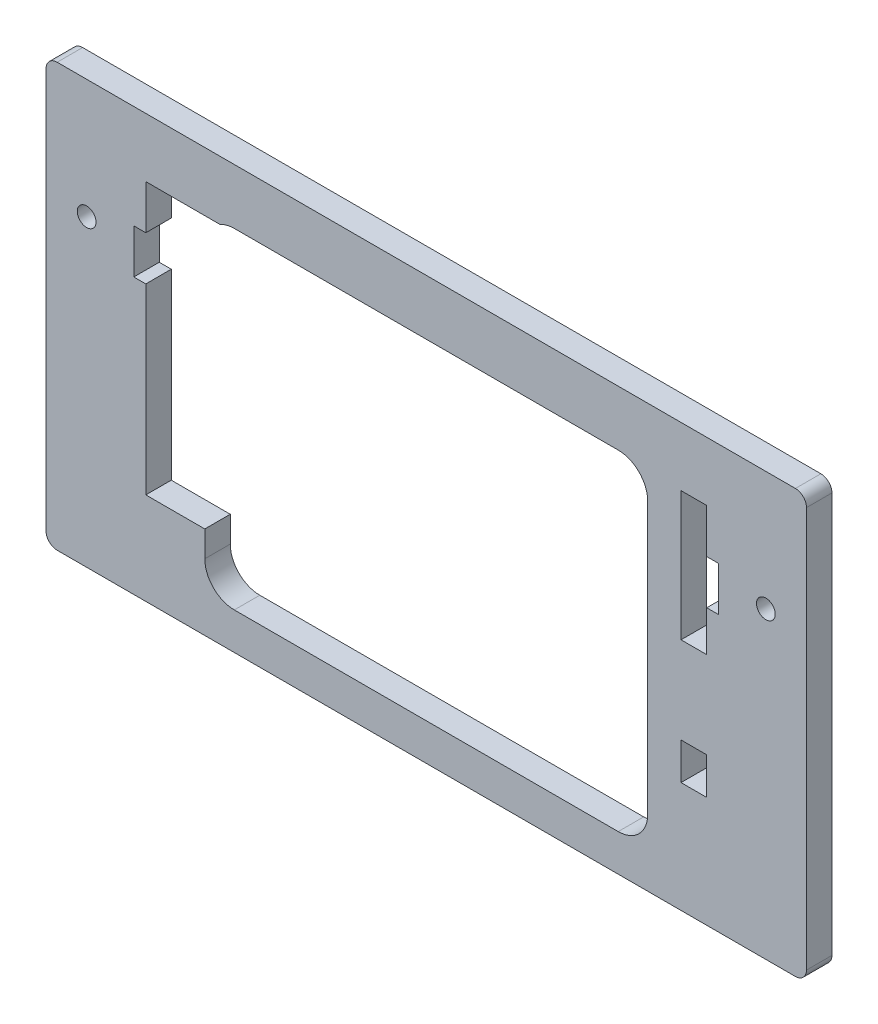
SolidWorks part; units mm, degrees
ref_plane "Front Plane" through (0, 0, 0) normal (0, 0, 1) x (1, 0, 0)
ref_plane "Top Plane" through (0, 0, 0) normal (0, 1, 0) x (1, 0, 0)
ref_plane "Right Plane" through (0, 0, 0) normal (1, 0, 0) x (0, 0, -1)
sketch "Sketch1" plane through (0, 0, 0) normal (0, 0, 1) x (1, 0, 0)
  line L1 (103, 57.25) -> (-103, 57.25)
  line L2 (103, 57.25) -> (103, -57.25)
  line L3 (103, -57.25) -> (-103, -57.25)
  line L4 (-103, 57.25) -> (-103, -57.25)
  line L5 (103, 57.25) -> (-103, -57.25) construction
  line L6 (103, -57.25) -> (-103, 57.25) construction
  point P0 (0, 0)
  dimension "D1" = 114.5
  dimension "D2" = 206
extrude "Boss-Extrude1" add sketch "Sketch1" against normal blind 6.9
sketch "Sketch2" plane through (0, 0, 0) normal (0, 0, 1) x (1, 0, 0)
  line L0 (103, 57.25) -> (-103, 57.25) construction
  line L1 (60, -45.75) -> (-60, -45.75)
  line L2 (60, -45.75) -> (60, 42.25)
  line L3 (60, 42.25) -> (-60, 42.25)
  line L4 (-60, -45.75) -> (-60, 42.25)
  line L5 (60, -45.75) -> (-60, 42.25) construction
  line L6 (60, 42.25) -> (-60, -45.75) construction
  point P0 (0, -1.75)
  dimension "D1" = 15
  dimension "D2" = 88
  dimension "D3" = 120
extrude "Cut-Extrude1" cut sketch "Sketch2" against normal through all
fillet "Fillet1" radius 8 4 edges at (60, 42.25, -3.45) (60, -45.75, -3.45) (-60, -45.75, -3.45) (-60, 42.25, -3.45)
sketch "Sketch3" plane through (0, 0, 0) normal (0, 0, 1) x (1, 0, 0)
  line L0 (103, 57.25) -> (-103, 57.25) construction
  line L1 (-91.775, 78.25) -> (-88.225, 78.25)
  line L2 (-91.775, 78.25) -> (-91.775, 36.25)
  line L3 (-91.775, 36.25) -> (-88.225, 36.25)
  line L4 (-88.225, 78.25) -> (-88.225, 36.25)
  line L5 (-91.775, 78.25) -> (-88.225, 36.25) construction
  line L6 (-91.775, 36.25) -> (-88.225, 78.25) construction
  point P0 (-90, 57.25)
  dimension "D1" = 3.55
  dimension "D2" = 21
  dimension "D3" = 90
extrude "Cut-Extrude2" [suppressed] cut sketch "Sketch3" against normal through all
sketch "Sketch4" plane through (0, 0, 0) normal (0, 0, 1) x (1, 0, 0)
  line L0 (103, 57.25) -> (-103, 57.25) construction
  line L1 (-93.81, 46.25) -> (-86.19, 46.25)
  line L2 (-93.81, 46.25) -> (-93.81, 41.25)
  line L3 (-93.81, 41.25) -> (-86.19, 41.25)
  line L4 (-86.19, 46.25) -> (-86.19, 41.25)
  line L5 (-93.81, 46.25) -> (-86.19, 41.25) construction
  line L6 (-93.81, 41.25) -> (-86.19, 46.25) construction
  point P0 (-90, 43.75)
  dimension "D1" = 7.62
  dimension "D2" = 5
  dimension "D3" = 11
extrude "Cut-Extrude3" [suppressed] cut sketch "Sketch4" against normal through all
sketch "Sketch5" plane through (0, 0, 0) normal (0, 0, 1) x (1, 0, 0)
  line L0 (103, 57.25) -> (-103, 57.25) construction
  line L1 (-65, 57.25) -> (-50, 57.25)
  line L2 (-65, 57.25) -> (-65, 63.75)
  line L3 (-65, 63.75) -> (-50, 63.75)
  line L4 (-50, 57.25) -> (-50, 63.75)
  line L7 (0, 57.25) -> (-7.5, 57.25)
  line L8 (0, 57.25) -> (0, 63.75)
  line L9 (0, 63.75) -> (-7.5, 63.75)
  line L10 (-7.5, 57.25) -> (-7.5, 63.75)
  dimension "D1" = 6.5
  dimension "D2" = 15
  dimension "D3" = 57.5
  dimension "D4" = 7.5
extrude "Boss-Extrude2" [suppressed] add sketch "Sketch5" against normal up to surface (6.9 mm away)
mirror "Mirror1" [suppressed] about plane through (0, 0, 0) normal (0, 1, 0)
sketch "Sketch7" plane through (0, 0, 0) normal (0, 0, 1) x (1, 0, 0)
  line L0 (-92, 25) -> (-92, -25) construction
  line L1 (-92, 0) -> (0, 0) construction
  circle A0 centre (-92, 25) radius 2.54
  circle A1 centre (-92, -25) radius 2.54 construction
  dimension "D3" = 5.08
  dimension "D1" = 92
  dimension "D2" = 50
extrude "Cut-Extrude5" cut sketch "Sketch7" against normal through all
sketch "Sketch9" plane through (0, 0, 0) normal (0, 0, 1) x (1, 0, 0)
  line L1 (-75.98, 41.25) -> (-69.02, 41.25)
  line L2 (-75.98, 41.25) -> (-75.98, 6.25)
  line L3 (-75.98, 6.25) -> (-69.02, 6.25)
  line L4 (-69.02, 41.25) -> (-69.02, 6.25)
  line L5 (-75.98, 41.25) -> (-69.02, 6.25) construction
  line L6 (-75.98, 6.25) -> (-69.02, 41.25) construction
  line L7 (-103, -57.25) -> (103, -57.25) construction
  line L8 (-75.98, -17.25) -> (-69.02, -17.25)
  line L9 (-75.98, -17.25) -> (-75.98, -27.25)
  line L10 (-75.98, -27.25) -> (-69.02, -27.25)
  line L11 (-69.02, -17.25) -> (-69.02, -27.25)
  line L12 (-75.98, -17.25) -> (-69.02, -27.25) construction
  line L13 (-75.98, -27.25) -> (-69.02, -17.25) construction
  point P0 (-72.5, 23.75)
  point P8 (-72.5, -22.25)
  dimension "D1" = 35
  dimension "D2" = 6.96
  dimension "D3" = 72.5
  dimension "D4" = 68.5
  dimension "D5" = 10
  dimension "D6" = 30
extrude "Cut-Extrude7" cut sketch "Sketch9" against normal through all
sketch "Sketch11" plane through (0, 0, 0) normal (0, 0, 1) x (1, 0, 0)
  line L0 (-75.98, 41.25) -> (-75.98, 6.25) construction
  line L1 (-75.98, 29.25) -> (-79.23, 29.25)
  line L2 (-75.98, 29.25) -> (-75.98, 17.25)
  line L3 (-75.98, 17.25) -> (-79.23, 17.25)
  line L4 (-79.23, 29.25) -> (-79.23, 17.25)
  line L5 (-69.02, 41.25) -> (-75.98, 41.25) construction
  point P6 (-72.5, 41.25)
  dimension "D1" = 3.25
  dimension "D2" = 12
  dimension "D3" = 12
extrude "Cut-Extrude8" cut sketch "Sketch11" against normal through all
mirror "Mirror2" about plane through (0, 0, 0) normal (1, 0, 0) of "Cut-Extrude8", "Cut-Extrude5", "Cut-Extrude7"
fillet "Fillet2" radius 3 4 edges at (103, 57.25, -3.45) (103, -57.25, -3.45) (-103, -57.25, -3.45) (-103, 57.25, -3.45)
sketch "Sketch8" plane through (0, 0, 0) normal (0, 0, 1) x (1, 0, 0)
  line L0 (-72, -36.75) -> (72, -36.75) construction
  line L1 (-100, -57.25) -> (100, -57.25) construction
  circle A0 centre (72, -36.75) radius 1.775
  circle A1 centre (-72, -36.75) radius 1.775
  point P4 (0, -36.75)
  dimension "D1" = 3.55
  dimension "D2" = 144
  dimension "D3" = 20.5
extrude "Cut-Extrude6" cut sketch "Sketch8" against normal through all
sketch "Sketch10" plane through (0, 0, 0) normal (0, 0, 1) x (1, 0, 0)
  line L0 (-100, -57.25) -> (100, -57.25) construction
  line L1 (-41.8, -57.25) -> (-35, -57.25)
  line L2 (-41.8, -57.25) -> (-41.8, -60.25)
  line L3 (-41.8, -60.25) -> (-35, -60.25)
  line L4 (-35, -57.25) -> (-35, -60.25)
  line L5 (0, 0) -> (0, -33.8944) construction
  line L6 (35, -57.25) -> (35, -60.25)
  line L7 (41.8, -60.25) -> (35, -60.25)
  line L8 (41.8, -57.25) -> (41.8, -60.25)
  line L9 (41.8, -57.25) -> (35, -57.25)
  line L10 (-35, -57.25) -> (-35, -35.0742) construction
  dimension "D1" = 3
  dimension "D2" = 35
  dimension "D3" = 6.8
extrude "Boss-Extrude3" add sketch "Sketch10" against normal up to surface (6.9 mm away) up to face at (-70.225, -36.75, -6.9)
fillet "Fillet3" radius 1.5 4 edges at (41.8, -60.25, -3.45) (35, -60.25, -3.45) (-35, -60.25, -3.45) (-41.8, -60.25, -3.45)
sketch "Sketch12" plane through (0, 0, 0) normal (0, 0, 1) x (1, 0, 0)
  text T0 "SeeMeCNC  87912  R1" font "1CamBam_Stick_9" height 2.5
sketch "Sketch13" plane through (0, 0, 0) normal (0, 0, 1) x (1, 0, 0)
  line L0 (52, 42.25) -> (-52, 42.25) construction
  line L1 (60, -37.75) -> (60, 34.25) construction
  line L2 (-52, -45.75) -> (52, -45.75) construction
  line L3 (-60, 34.25) -> (-60, -37.75) construction
  line L4 (52, 42.25) -> (-52, 42.25)
  line L5 (60, -37.75) -> (60, 34.25)
  line L6 (-52, -45.75) -> (52, -45.75)
  line L7 (-60, 34.25) -> (-60, -37.75)
  line L8 (-35, -57.25) -> (35, -57.25) construction
  line L9 (41.8, -57.25) -> (100, -57.25) construction
  line L10 (-100, -57.25) -> (-41.8, -57.25) construction
  line L11 (-35, -57.25) -> (35, -57.25)
  line L12 (41.8, -57.25) -> (100, -57.25)
  line L13 (-100, -57.25) -> (-41.8, -57.25)
  line L14 (-41.8, -57.25) -> (-35, -57.25)
  line L15 (35, -57.25) -> (41.8, -57.25)
  line L17 (-60, -37.75) -> (60, -37.75)
  line L18 (-60, -37.75) -> (-60, -39.25)
  line L19 (-52, -47.25) -> (52, -47.25)
  line L20 (60, -37.75) -> (60, -39.25)
  line L21 (-60, -37.75) -> (60, -47.25) construction
  line L22 (-60, -47.25) -> (60, -37.75) construction
  line L26 (36.5, -60.25) -> (40.3, -60.25)
  line L27 (41.8, -58.75) -> (41.8, -57.25)
  line L28 (41.8, -57.25) -> (100, -57.25)
  line L29 (103, -54.25) -> (103, 54.25)
  line L30 (100, 57.25) -> (-100, 57.25)
  line L31 (-103, 54.25) -> (-103, -54.25)
  line L32 (-100, -57.25) -> (-41.8, -57.25)
  line L33 (-41.8, -57.25) -> (-41.8, -58.75)
  line L34 (-40.3, -60.25) -> (-36.5, -60.25)
  line L35 (-35, -58.75) -> (-35, -57.25)
  line L36 (-35, -57.25) -> (35, -57.25)
  line L37 (35, -57.25) -> (35, -58.75)
  line L38 (36.5, -60.25) -> (40.3, -60.25)
  line L39 (41.8, -58.75) -> (41.8, -57.25)
  line L40 (41.8, -57.25) -> (100, -57.25)
  line L41 (103, -54.25) -> (103, 54.25)
  line L42 (100, 57.25) -> (-100, 57.25)
  line L43 (-103, 54.25) -> (-103, -54.25)
  line L44 (-100, -57.25) -> (-41.8, -57.25)
  line L45 (-41.8, -57.25) -> (-41.8, -58.75)
  line L46 (-40.3, -60.25) -> (-36.5, -60.25)
  line L47 (-35, -58.75) -> (-35, -57.25)
  line L48 (-35, -57.25) -> (35, -57.25)
  line L49 (35, -57.25) -> (35, -58.75)
  arc A0 (60, 34.25) -> (52, 42.25) centre (52, 34.25) ccw construction
  arc A1 (-52, 42.25) -> (-60, 34.25) centre (-52, 34.25) ccw construction
  arc A2 (52, -45.75) -> (60, -37.75) centre (52, -37.75) ccw construction
  arc A3 (-60, -37.75) -> (-52, -45.75) centre (-52, -37.75) ccw construction
  arc A4 (60, 34.25) -> (52, 42.25) centre (52, 34.25) ccw
  arc A5 (-52, 42.25) -> (-60, 34.25) centre (-52, 34.25) ccw
  arc A6 (52, -45.75) -> (60, -37.75) centre (52, -37.75) ccw
  arc A7 (-60, -37.75) -> (-52, -45.75) centre (-52, -37.75) ccw
  arc A8 (52, -47.25) -> (60, -39.25) centre (52, -39.25) ccw
  arc A9 (-60, -39.25) -> (-52, -47.25) centre (-52, -39.25) ccw
  arc A16 (40.3, -60.25) -> (41.8, -58.75) centre (40.3, -58.75) ccw
  arc A17 (100, -57.25) -> (103, -54.25) centre (100, -54.25) ccw
  arc A18 (103, 54.25) -> (100, 57.25) centre (100, 54.25) ccw
  arc A19 (-100, 57.25) -> (-103, 54.25) centre (-100, 54.25) ccw
  arc A20 (-103, -54.25) -> (-100, -57.25) centre (-100, -54.25) ccw
  arc A21 (-41.8, -58.75) -> (-40.3, -60.25) centre (-40.3, -58.75) ccw
  arc A22 (-36.5, -60.25) -> (-35, -58.75) centre (-36.5, -58.75) ccw
  arc A23 (35, -58.75) -> (36.5, -60.25) centre (36.5, -58.75) ccw
  arc A24 (40.3, -60.25) -> (41.8, -58.75) centre (40.3, -58.75) ccw
  arc A25 (100, -57.25) -> (103, -54.25) centre (100, -54.25) ccw
  arc A26 (103, 54.25) -> (100, 57.25) centre (100, 54.25) ccw
  arc A27 (-100, 57.25) -> (-103, 54.25) centre (-100, 54.25) ccw
  arc A28 (-103, -54.25) -> (-100, -57.25) centre (-100, -54.25) ccw
  arc A29 (-41.8, -58.75) -> (-40.3, -60.25) centre (-40.3, -58.75) ccw
  arc A30 (-36.5, -60.25) -> (-35, -58.75) centre (-36.5, -58.75) ccw
  arc A31 (35, -58.75) -> (36.5, -60.25) centre (36.5, -58.75) ccw
  point P26 (0, -42.5)
  dimension "D2" = 10
  dimension "D3" = 8
  dimension "D1" = 0
extrude "Cut-Extrude9" cut sketch "Sketch13" against normal through all contours L46 A30 L47 L14 L45 A29 | L49 A31 L38 A24 L39 L15 | L18 A9 L19 A8 L20 A6 L6 A7
sketch "Sketch14" plane through (0, 0, 0) normal (0, 0, 1) x (1, 0, 0)
  line L0 (-103, 54.25) -> (-103, -54.25) construction
  line L1 (-75.98, 6.25) -> (-69.02, 6.25) construction
  line L2 (-69.02, 41.25) -> (-75.98, 41.25) construction
  line L3 (-69.02, 6.25) -> (-69.02, 41.25) construction
  line L4 (-103, 54.25) -> (-103, -54.25)
  line L5 (-75.98, 6.25) -> (-69.02, 6.25)
  line L6 (-69.02, 41.25) -> (-75.98, 41.25)
  line L7 (-69.02, 6.25) -> (-69.02, 41.25)
  line L8 (-60, 34.25) -> (-60, -39.25) construction
  line L9 (-60, -32.25) -> (-75.98, -32.25)
  line L10 (-60, -32.25) -> (-60, 41.25)
  line L11 (-60, 41.25) -> (-75.98, 41.25)
  line L12 (-75.98, -32.25) -> (-75.98, 41.25)
  line L13 (-60, -32.25) -> (-75.98, 41.25) construction
  line L14 (-60, 41.25) -> (-75.98, -32.25) construction
  line L15 (-60, 34.25) -> (-60, -39.25)
  line L16 (-60, 41.25) -> (-55.873, 41.25)
  line L17 (-100, -57.25) -> (100, -57.25) construction
  arc A0 (-52, 42.25) -> (-60, 34.25) centre (-52, 34.25) ccw construction
  arc A1 (-52, 42.25) -> (-60, 34.25) centre (-52, 34.25) ccw
  point P10 (-67.99, 4.5)
  line M8 (-60, -39.25) -> (-60, 34.25)
  arc M9 (-60, 34.25) -> (-52, 42.25) centre (-52, 34.25) cw
  line M32 (-69.02, 41.25) -> (-69.02, 6.25)
  line M33 (-69.02, 6.25) -> (-75.98, 6.25)
  dimension "D1" = 25
extrude "Cut-Extrude10" cut sketch "Sketch14" against normal through all contours L12 L9 L10 L11 M8 M32 M33 | L16 L10 M9
sketch "Sketch15" plane through (0, 0, 0) normal (0, 0, 1) x (1, 0, 0)
  circle A0 centre (72, -36.75) radius 1.775 construction
  circle A1 centre (-72, -36.75) radius 1.775 construction
  circle A2 centre (72, -36.75) radius 1.775
  circle A3 centre (-72, -36.75) radius 1.775
extrude "Boss-Extrude4" add sketch "Sketch15" against normal up to surface (6.9 mm away) up to face at (-70.225, -36.75, -6.9)
